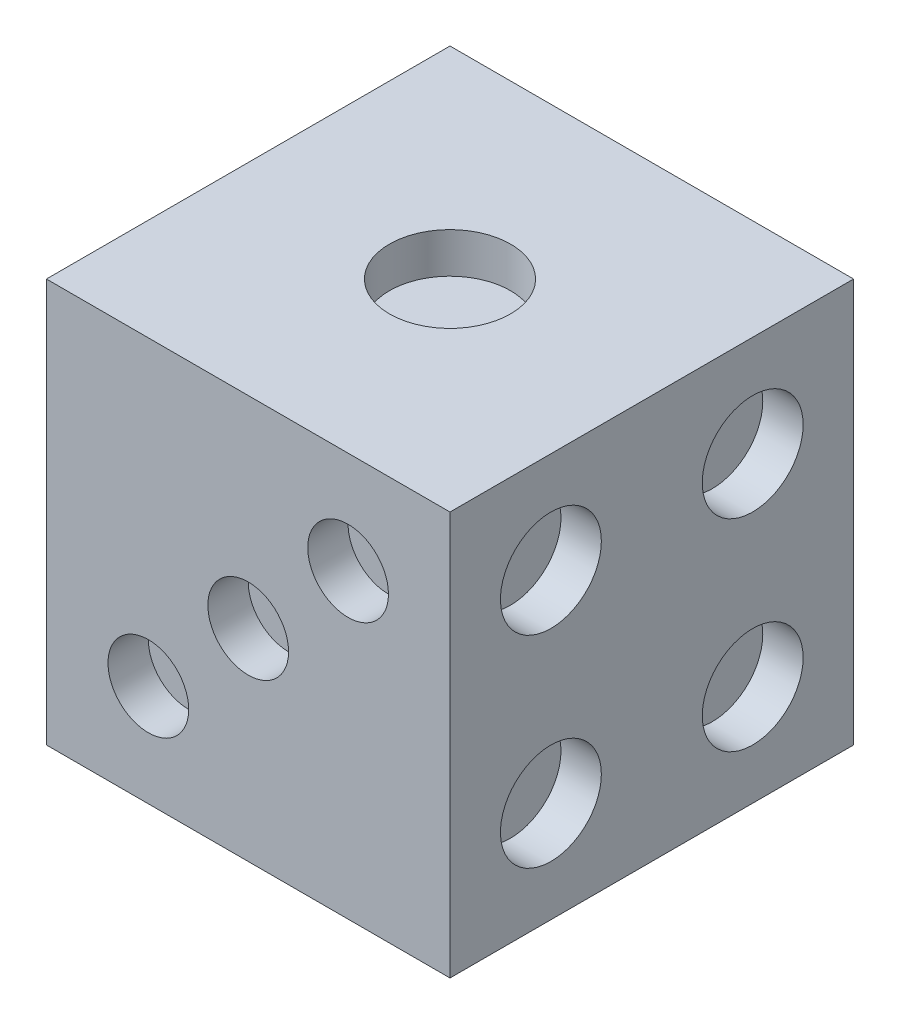
SolidWorks part; units mm, degrees
ref_plane "Front Plane" through (0, 0, 0) normal (0, 0, 1) x (1, 0, 0)
ref_plane "Top Plane" through (0, 0, 0) normal (0, 1, 0) x (1, 0, 0)
ref_plane "Right Plane" through (0, 0, 0) normal (1, 0, 0) x (0, 0, -1)
sketch "Sketch1" plane through (0, 0, 0) normal (0, 1, 0) x (1, 0, 0)
  line L5 (50, -50) -> (-50, -50)
  line L6 (50, -50) -> (50, 50)
  line L7 (50, 50) -> (-50, 50)
  line L8 (-50, -50) -> (-50, 50)
  line L9 (50, -50) -> (-50, 50) construction
  line L10 (50, 50) -> (-50, -50) construction
  point P0 (0, 0)
  dimension "D1" = 100
  dimension "D2" = 100
  dimension "D3" = 50
  dimension "D4" = 50
extrude "Boss-Extrude1" add sketch "Sketch1" along normal blind 100 contours L8 L7 L6 L5
sketch "Sketch3" plane through (0, 100, 0) normal (0, 1, 0) x (1, 0, 0)
  circle A0 centre (0, 0) radius 15
  dimension "D1" = 30
extrude "Cut-Extrude1" cut sketch "Sketch3" against normal blind 10 contours A0
sketch "Sketch5" plane through (0, 0, 50) normal (0, 0, 1) x (1, 0, 0)
  line L0 (50, 100) -> (-50, 0) construction
  circle A0 centre (0, 50) radius 10
  circle A1 centre (24.7487, 74.7487) radius 10
  circle A2 centre (-24.7487, 25.2513) radius 10
  point P12 (4.7004, 67.1103)
  dimension "D1" = 35
  dimension "D2" = 35
extrude "Cut-Extrude2" cut sketch "Sketch5" against normal blind 10 contours A1 | A0 | A2
sketch "Sketch8" plane through (-50, 0, 0) normal (-1, 0, 0) x (0, 0, 1)
  line L0 (-50, 100) -> (50, 0) construction
  circle A0 centre (-16.9706, 66.9706) radius 13
  circle A1 centre (16.9706, 33.0294) radius 13
  point P8 (0, 50)
  dimension "D1" = 48
  dimension "D2" = 24
extrude "Cut-Extrude3" cut sketch "Sketch8" against normal blind 10 contours A1 | A0
sketch "Sketch12" plane through (50, 0, 0) normal (1, 0, 0) x (0, 0, -1)
  line L0 (-50, 100) -> (50, 0) construction
  line L1 (50, 0) -> (50, 100) construction
  line L2 (50, 100) -> (-50, 0) construction
  line L3 (-50, 0) -> (-50, 100) construction
  line L5 (25, 25) -> (-25, 25) construction
  line L6 (25, 25) -> (25, 75) construction
  line L7 (25, 75) -> (-25, 75) construction
  line L8 (-25, 25) -> (-25, 75) construction
  line L9 (25, 25) -> (-25, 75) construction
  line L10 (25, 75) -> (-25, 25) construction
  circle A0 centre (-25, 75) radius 12.5
  circle A1 centre (25, 75) radius 12.5
  circle A2 centre (25, 25) radius 12.5
  circle A3 centre (-25, 25) radius 12.5
  point P8 (0, 50)
  dimension "D3" = 25
  dimension "D1" = 50
  dimension "D2" = 50
extrude "Cut-Extrude4" cut sketch "Sketch12" against normal blind 10 contours A2 | A1 | A0 | A3
sketch "Sketch13" plane through (0, 0, -50) normal (0, 0, -1) x (-1, 0, 0)
  line L0 (-50, 100) -> (50, 0) construction
  line L1 (50, 0) -> (50, 100) construction
  line L2 (50, 100) -> (-50, 0) construction
  line L3 (-50, 0) -> (-50, 100) construction
  line L5 (27.5, 22.5) -> (-27.5, 22.5) construction
  line L6 (27.5, 22.5) -> (27.5, 77.5) construction
  line L7 (27.5, 77.5) -> (-27.5, 77.5) construction
  line L8 (-27.5, 22.5) -> (-27.5, 77.5) construction
  line L9 (27.5, 22.5) -> (-27.5, 77.5) construction
  line L10 (27.5, 77.5) -> (-27.5, 22.5) construction
  circle A0 centre (0, 50) radius 10
  circle A1 centre (-27.5, 77.5) radius 10
  circle A2 centre (27.5, 77.5) radius 10
  circle A3 centre (27.5, 22.5) radius 10
  circle A4 centre (-27.5, 22.5) radius 10
  point P8 (0, 50)
  dimension "D1" = 55
extrude "Cut-Extrude5" cut sketch "Sketch13" against normal blind 10
sketch "Sketch14" plane through (0, 0, 0) normal (0, -1, 0) x (-1, 0, 0)
  line L0 (-16.67, 50) -> (-16.67, -50) construction
  line L1 (-50, 50) -> (50, 50) construction
  line L2 (-50, -50) -> (50, -50) construction
  line L3 (-50, -50) -> (-50, 50) construction
  line L4 (16.67, 50) -> (16.67, -50) construction
  line L5 (50, -50) -> (50, 50) construction
  line L6 (-50, -25) -> (50, -25) construction
  line L7 (-50, 25) -> (50, 25) construction
  line L8 (-50, 0) -> (50, 0) construction
  circle A0 centre (-16.67, 0) radius 10
  circle A1 centre (16.67, 0) radius 10
  circle A2 centre (16.67, 25) radius 10
  circle A3 centre (-16.67, 25) radius 10
  circle A4 centre (-16.67, -25) radius 10
  circle A5 centre (16.67, -25) radius 10
  dimension "D1" = 33.33
  dimension "D2" = 33.33
  dimension "D3" = 25
  dimension "D4" = 25
  dimension "D5" = 25
  dimension "D6" = 25
extrude "Cut-Extrude6" cut sketch "Sketch14" against normal blind 10
